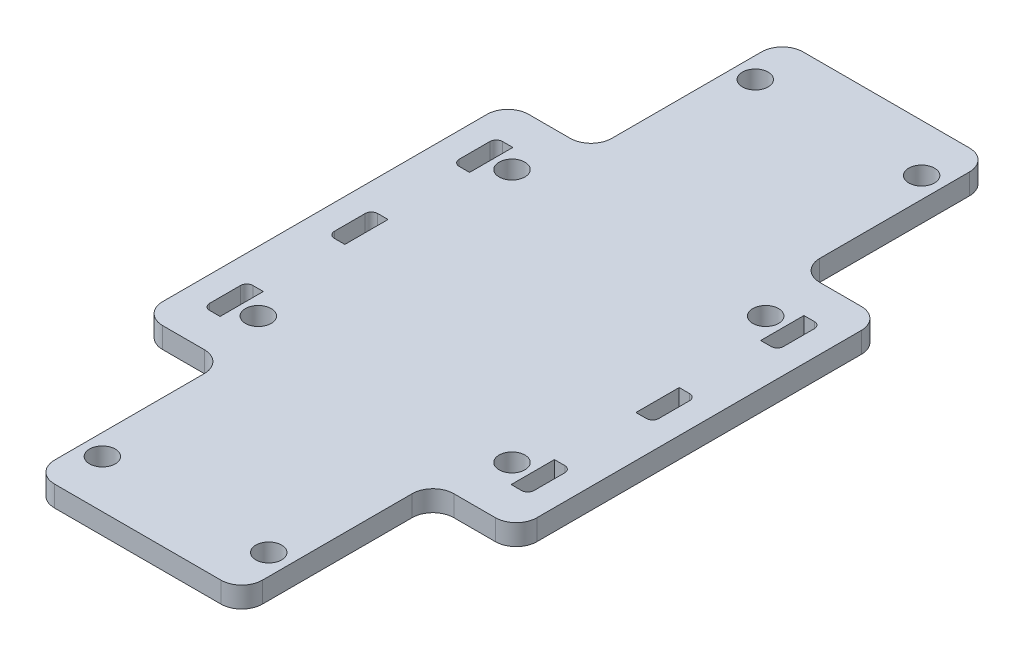
SolidWorks part; units mm, degrees
ref_plane "Front Plane" through (0, 0, 0) normal (0, 0, 1) x (1, 0, 0)
ref_plane "Top Plane" through (0, 0, 0) normal (0, 1, 0) x (1, 0, 0)
ref_plane "Right Plane" through (0, 0, 0) normal (1, 0, 0) x (0, 0, -1)
sketch "Sketch1" plane through (0, 0, 0) normal (0, 1, 0) x (1, 0, 0)
  line L1 (15.25, -15.25) -> (-15.25, -15.25) construction
  line L2 (15.25, -15.25) -> (15.25, 15.25) construction
  line L3 (15.25, 15.25) -> (-15.25, 15.25) construction
  line L4 (-15.25, -15.25) -> (-15.25, 15.25) construction
  line L5 (15.25, -15.25) -> (-15.25, 15.25) construction
  line L6 (15.25, 15.25) -> (-15.25, -15.25) construction
  line L7 (12.5, -45) -> (-12.5, -45)
  line L8 (22.5, -22) -> (22.5, 22)
  line L9 (12.5, 45) -> (-12.5, 45)
  line L10 (-22.5, -22) -> (-22.5, 22)
  line L11 (22.5, -45) -> (-22.5, 45) construction
  line L12 (22.5, 45) -> (-22.5, -45) construction
  line L16 (0, 0) -> (0, 58.5493) construction
  line L17 (0, 0) -> (-59.7309, 0) construction
  line L19 (-12.5, 45) -> (-12.5, 22)
  line L20 (12.5, 22) -> (12.5, 45)
  line L21 (-12.5, 22) -> (-22.5, 22)
  line L22 (-22.5, -22) -> (-12.5, -22)
  line L26 (0, 0) -> (0, -75.0204) construction
  line L27 (12.5, 22) -> (22.5, 22)
  line L28 (-12.5, -45) -> (-12.5, -22)
  line L29 (12.5, -45) -> (12.5, -22)
  line L30 (22.5, -22) -> (12.5, -22)
  point P0 (0, 0)
  point P6 (0, 0)
  point P12 (0, -45)
  point P17 (0, 45)
  dimension "D5" = 25
  dimension "D8" = 22
  dimension "D1" = 30.5
  dimension "D2" = 30.5
  dimension "D3" = 45
  dimension "D4" = 90
  dimension "D6" = 25
  dimension "D7" = 22
extrude "Boss-Extrude1" add sketch "Sketch1" along normal blind 2.5
sketch "Sketch2" plane through (0, 2.5, 0) normal (0, 1, 0) x (1, 0, 0)
  line L0 (0, 0) -> (0, 78.022) construction
  line L1 (15.25, -15.25) -> (-15.25, 15.25) construction
  line L2 (0, 0) -> (40.3088, 0) construction
  circle A0 centre (-15.25, 15.25) radius 1.55
  circle A1 centre (15.25, 15.25) radius 1.55
  circle A2 centre (15.25, -15.25) radius 1.55
  circle A3 centre (-15.25, -15.25) radius 1.55
  circle A4 centre (-10, 39.25) radius 1.55
  circle A5 centre (-10, -39.25) radius 1.55
  circle A6 centre (10, -39.25) radius 1.55
  circle A7 centre (10, 39.25) radius 1.55
  dimension "D1" = 3.1
  dimension "D5" = 3.1
  dimension "D3" = 30.5
  dimension "D4" = 24
  dimension "D6" = 10
  dimension "D2" = 2
extrude "Cut-Extrude1" cut sketch "Sketch2" against normal through all
sketch "Sketch3" plane through (0, 2.5, 0) normal (0, 1, 0) x (1, 0, 0)
  line L0 (37.5278, 0) -> (-37.5278, 0) construction
  line L2 (0, -47.5507) -> (0, 47.5507) construction
  line L4 (18.5, 0) -> (-18.5, 0) construction
  line L5 (-18.5, -31.1048) -> (-18.5, 31.1048) construction
  line L6 (-17.5, -2.6) -> (-18.75, -2.6)
  line L7 (-17.5, -2.6) -> (-17.5, 2.6)
  line L8 (-17.5, 2.6) -> (-18.75, 2.6)
  line L9 (-19.5, -1.85) -> (-19.5, 1.85)
  line L10 (-17.5, -2.6) -> (-19.5, 2.6) construction
  line L11 (-17.5, 2.6) -> (-19.5, -2.6) construction
  line L12 (-17.5, 12.4) -> (-18.75, 12.4)
  line L13 (-17.5, 12.4) -> (-17.5, 17.6)
  line L14 (-17.5, 17.6) -> (-18.75, 17.6)
  line L15 (-19.5, 13.15) -> (-19.5, 16.85)
  line L16 (18.5, 15) -> (-18.5, 15) construction
  line L17 (-17.5, 12.4) -> (-19.5, 17.6) construction
  line L18 (-17.5, 17.6) -> (-19.5, 12.4) construction
  line L19 (-17.5, 27.4) -> (-18.75, 27.4)
  line L20 (-17.5, 27.4) -> (-17.5, 32.6)
  line L21 (-17.5, 32.6) -> (-18.75, 32.6)
  line L22 (-19.5, 28.15) -> (-19.5, 31.85)
  line L23 (18.5, 30) -> (-18.5, 30) construction
  line L24 (-17.5, 27.4) -> (-19.5, 32.6) construction
  line L25 (-17.5, 32.6) -> (-19.5, 27.4) construction
  line L26 (17.5, 32.6) -> (19.5, 27.4) construction
  line L27 (17.5, 27.4) -> (19.5, 32.6) construction
  line L28 (17.5, 17.6) -> (19.5, 12.4) construction
  line L29 (17.5, 12.4) -> (19.5, 17.6) construction
  line L30 (17.5, 2.6) -> (19.5, -2.6) construction
  line L31 (17.5, -2.6) -> (19.5, 2.6) construction
  line L32 (19.5, 28.15) -> (19.5, 31.85)
  line L33 (17.5, 32.6) -> (18.75, 32.6)
  line L34 (17.5, 27.4) -> (17.5, 32.6)
  line L35 (17.5, 27.4) -> (18.75, 27.4)
  line L36 (19.5, 13.15) -> (19.5, 16.85)
  line L37 (17.5, 17.6) -> (18.75, 17.6)
  line L38 (17.5, 12.4) -> (17.5, 17.6)
  line L39 (17.5, 12.4) -> (18.75, 12.4)
  line L40 (19.5, -1.85) -> (19.5, 1.85)
  line L41 (17.5, 2.6) -> (18.75, 2.6)
  line L42 (17.5, -2.6) -> (17.5, 2.6)
  line L43 (17.5, -2.6) -> (18.75, -2.6)
  line L44 (18.5, -30) -> (-18.5, -30) construction
  line L45 (17.5, -12.4) -> (19.5, -17.6) construction
  line L46 (17.5, -17.6) -> (19.5, -12.4) construction
  line L47 (17.5, -27.4) -> (19.5, -32.6) construction
  line L48 (17.5, -32.6) -> (19.5, -27.4) construction
  line L49 (-17.5, -32.6) -> (-19.5, -27.4) construction
  line L50 (-17.5, -27.4) -> (-19.5, -32.6) construction
  line L51 (-17.5, -17.6) -> (-19.5, -12.4) construction
  line L52 (-17.5, -12.4) -> (-19.5, -17.6) construction
  line L53 (18.5, -15) -> (-18.5, -15) construction
  line L54 (17.5, -12.4) -> (18.75, -12.4)
  line L55 (17.5, -12.4) -> (17.5, -17.6)
  line L56 (17.5, -17.6) -> (18.75, -17.6)
  line L57 (19.5, -13.15) -> (19.5, -16.85)
  line L58 (17.5, -27.4) -> (18.75, -27.4)
  line L59 (17.5, -27.4) -> (17.5, -32.6)
  line L60 (17.5, -32.6) -> (18.75, -32.6)
  line L61 (19.5, -28.15) -> (19.5, -31.85)
  line L62 (-19.5, -28.15) -> (-19.5, -31.85)
  line L63 (-17.5, -32.6) -> (-18.75, -32.6)
  line L64 (-17.5, -27.4) -> (-17.5, -32.6)
  line L65 (-17.5, -27.4) -> (-18.75, -27.4)
  line L66 (-19.5, -13.15) -> (-19.5, -16.85)
  line L67 (-17.5, -17.6) -> (-18.75, -17.6)
  line L68 (-17.5, -12.4) -> (-17.5, -17.6)
  line L69 (-17.5, -12.4) -> (-18.75, -12.4)
  arc A0 (-18.75, -2.6) -> (-19.5, -1.85) centre (-18.75, -1.85) cw
  arc A1 (-18.75, 2.6) -> (-19.5, 1.85) centre (-18.75, 1.85) ccw
  arc A2 (-18.75, 12.4) -> (-19.5, 13.15) centre (-18.75, 13.15) cw
  arc A3 (-18.75, 17.6) -> (-19.5, 16.85) centre (-18.75, 16.85) ccw
  arc A4 (-18.75, 27.4) -> (-19.5, 28.15) centre (-18.75, 28.15) cw
  arc A5 (-18.75, 32.6) -> (-19.5, 31.85) centre (-18.75, 31.85) ccw
  arc A6 (18.75, 32.6) -> (19.5, 31.85) centre (18.75, 31.85) cw
  arc A7 (18.75, 27.4) -> (19.5, 28.15) centre (18.75, 28.15) ccw
  arc A8 (18.75, 17.6) -> (19.5, 16.85) centre (18.75, 16.85) cw
  arc A9 (18.75, 12.4) -> (19.5, 13.15) centre (18.75, 13.15) ccw
  arc A10 (18.75, 2.6) -> (19.5, 1.85) centre (18.75, 1.85) cw
  arc A11 (18.75, -2.6) -> (19.5, -1.85) centre (18.75, -1.85) ccw
  arc A12 (18.75, -12.4) -> (19.5, -13.15) centre (18.75, -13.15) cw
  arc A13 (18.75, -17.6) -> (19.5, -16.85) centre (18.75, -16.85) ccw
  arc A14 (18.75, -27.4) -> (19.5, -28.15) centre (18.75, -28.15) cw
  arc A15 (18.75, -32.6) -> (19.5, -31.85) centre (18.75, -31.85) ccw
  arc A16 (-18.75, -32.6) -> (-19.5, -31.85) centre (-18.75, -31.85) cw
  arc A17 (-18.75, -27.4) -> (-19.5, -28.15) centre (-18.75, -28.15) ccw
  arc A18 (-18.75, -17.6) -> (-19.5, -16.85) centre (-18.75, -16.85) cw
  arc A19 (-18.75, -12.4) -> (-19.5, -13.15) centre (-18.75, -13.15) ccw
  point P4 (0, 0)
  point P8 (0, 0)
  point P11 (0, 0)
  point P18 (-18.5, 0)
  point P33 (-18.5, 15)
  point P46 (-18.5, 30)
  point P80 (18.5, 30)
  point P81 (18.5, 15)
  point P82 (18.5, 0)
  point P127 (18.5, -15)
  point P128 (18.5, -30)
  point P129 (-18.5, -30)
  point P130 (-18.5, -15)
  dimension "D4" = 0.75
  dimension "D1" = 37
  dimension "D2" = 2
  dimension "D3" = 5.2
  dimension "D5" = 3
extrude "Cut-Extrude2" cut sketch "Sketch3" against normal through all
fillet "Fillet2" radius 2.5 8 edges at (12.5, 1.25, -22) (22.5, 1.25, -22) (22.5, 1.25, 22) (12.5, 1.25, 22) (-12.5, 1.25, 22) (-22.5, 1.25, 22) (-12.5, 1.25, -22) (-22.5, 1.25, -22)
fillet "Fillet3" radius 2.5 4 edges at (12.5, 1.25, 45) (-12.5, 1.25, 45) (-12.5, 1.25, -45) (12.5, 1.25, -45)
